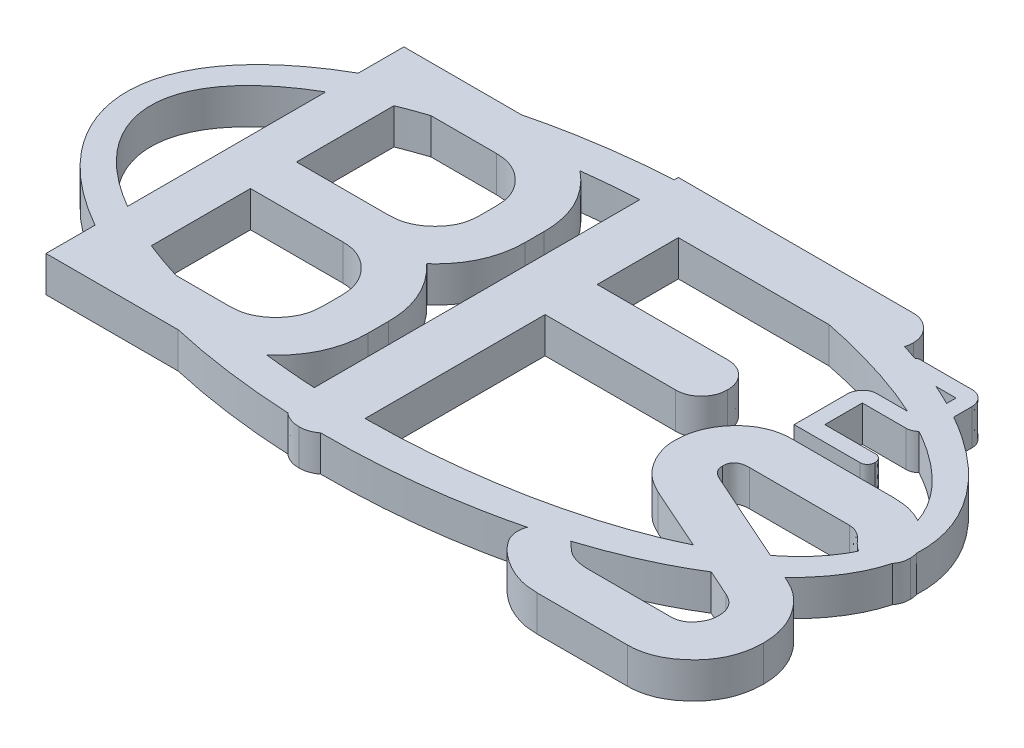
SolidWorks part; units mm, degrees
ref_plane "Front Plane" through (0, 0, 0) normal (0, 0, 1) x (1, 0, 0)
ref_plane "Top Plane" through (0, 0, 0) normal (0, 1, 0) x (1, 0, 0)
ref_plane "Right Plane" through (0, 0, 0) normal (1, 0, 0) x (0, 0, -1)
sketch "Sketch1" plane through (0, 0, 0) normal (0, 1, 0) x (1, 0, 0)
  line L0 (0, 42.3105) -> (0, 34.9449)
  line L1 (-84.6157, 0) -> (-79.5357, 0)
  line L2 (0, 42.3105) -> (0, 52.4705)
  line L3 (0, 42.3105) -> (-5.08, 42.3105)
  line L4 (0, 42.3105) -> (5.08, 42.3105)
  ellipse E0 centre (0, 0) end of major axis (84.6157, 0) minor radius 42.3105
  ellipse E1 centre (0, 0) end of major axis (-79.5357, 0) minor radius 34.9449
  dimension "D1" = 5.08
  dimension "D2" = 10.16
  dimension "D3" = 5.08
  dimension "D4" = 5.08
extrude "Boss-Extrude1" add sketch "Sketch1" along normal blind 7.62 contours E1 L0 E0 L1 | E1 L1 E0 L0
sketch "Sketch3" plane through (0, 7.62, 0) normal (0, 1, 0) x (1, 0, 0)
  text T0 "B" font "OCR A Extended" height 76.2
  text T1 "F" font "OCR A Extended" height 86.36
  text T2 "s" font "OCR A Extended" height 76.2
  text T3 "2" font "OCR A Extended" height 25.4
extrude "Boss-Extrude2" add sketch "Sketch3" against normal blind 7.62
scale "Scale1" bodies to scale 102 scale about centroid uniform scaling yes scale factor 1.43
sketch "Sketch9" plane through (0, 0, 0) normal (0, 1, 0) x (1, 0, 0)
  point P0 (-109.6491, 47.7852)
